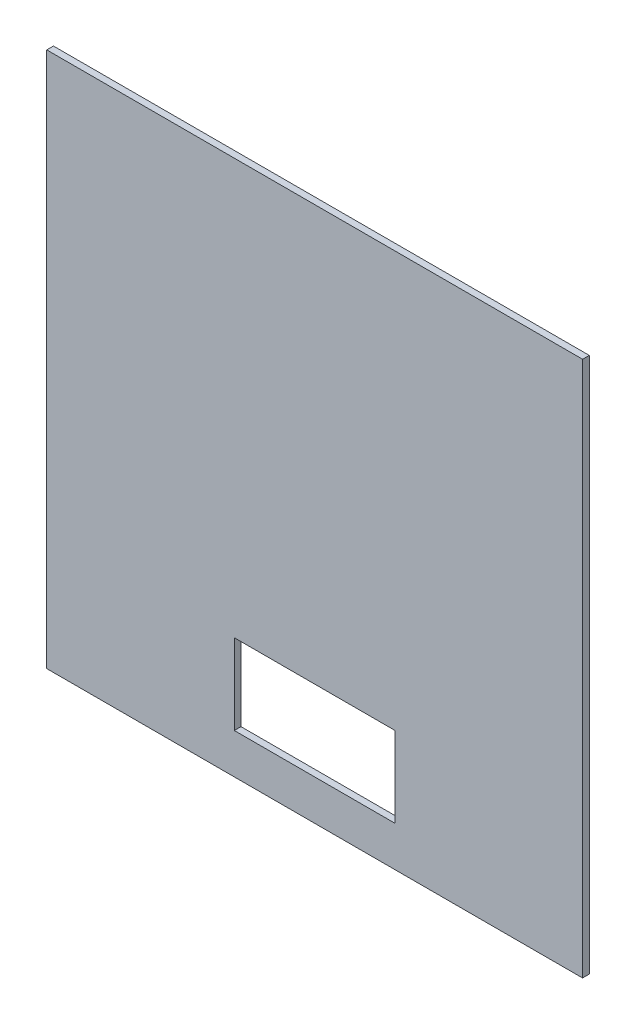
SolidWorks part; units mm, degrees
material "6061-T6 (SS)"
ref_plane "Front Plane" through (0, 0, 0) normal (0, 0, 1) x (1, 0, 0)
ref_plane "Top Plane" through (0, 0, 0) normal (0, 1, 0) x (1, 0, 0)
ref_plane "Right Plane" through (0, 0, 0) normal (1, 0, 0) x (0, 0, -1)
sketch "Sketch1" plane through (0, 0, 0) normal (0, 0, 1) x (1, 0, 0)
  line L0 (-259.5239, 0) -> (259.5239, 0) construction
  line L1 (0, -214.3934) -> (0, 214.3934) construction
  line L3 (-127, -127) -> (127, -127)
  line L4 (-127, -127) -> (-127, 127)
  line L5 (-127, 127) -> (127, 127)
  line L6 (127, -127) -> (127, 127)
  line L7 (-127, -127) -> (127, 127) construction
  line L8 (-127, 127) -> (127, -127) construction
  line L9 (-38.1, -107.95) -> (38.1, -107.95)
  line L10 (-38.1, -107.95) -> (-38.1, -69.85)
  line L11 (-38.1, -69.85) -> (38.1, -69.85)
  line L12 (38.1, -107.95) -> (38.1, -69.85)
  line L13 (-38.1, -107.95) -> (38.1, -69.85) construction
  line L14 (-38.1, -69.85) -> (38.1, -107.95) construction
  line L19 (-47.625, -47.625) -> (47.625, 47.625) construction
  line L20 (-47.625, 47.625) -> (47.625, -47.625) construction
  point P0 (0, 0)
  point P4 (0, 0)
  point P8 (0, 0)
  point P15 (0, -88.9)
  dimension "D1" = 254
  dimension "D2" = 254
  dimension "D4" = 19.05
  dimension "D5" = 76.2
  dimension "D6" = 38.1
  dimension "D7" = 95.25
  dimension "D8" = 95.25
extrude "Boss-Extrude1" add sketch "Sketch1" along normal mid plane 3.175
sketch "Sketch2" plane through (0, 0, 1.5875) normal (0, 0, 1) x (1, 0, 0)
  line L0 (-203.3385, 0) -> (203.3385, 0) construction
  line L1 (0, -160.1096) -> (0, 160.1096) construction
  line L2 (-127, 127) -> (127, 127) construction
  line L3 (-127, 127) -> (-107, 127)
  line L4 (-127, 127) -> (-127, 107)
  line L5 (-127, 107) -> (-107, 107)
  line L6 (-107, 127) -> (-107, 107)
  line L7 (-127, 127) -> (-107, 107) construction
  line L8 (-127, 107) -> (-107, 127) construction
  line L9 (-127, -127) -> (-127, 127) construction
  line L10 (127, 107) -> (107, 107)
  line L11 (107, 127) -> (107, 107)
  line L12 (127, 127) -> (127, 107)
  line L13 (127, 127) -> (107, 127)
  line L14 (107, -127) -> (107, -107)
  line L15 (127, -107) -> (107, -107)
  line L16 (127, -127) -> (107, -127)
  line L17 (127, -127) -> (127, -107)
  line L18 (-127, -107) -> (-107, -107)
  line L19 (-107, -127) -> (-107, -107)
  line L20 (-127, -127) -> (-127, -107)
  line L21 (-127, -127) -> (-107, -127)
  point P0 (-117, 117)
  point P5 (0, 0)
  point P9 (0, 0)
  point P33 (0, 0)
  dimension "D1" = 20
  dimension "D2" = 20
  dimension "D3" = 10
  dimension "D4" = 10
  dimension "D5" = 4
